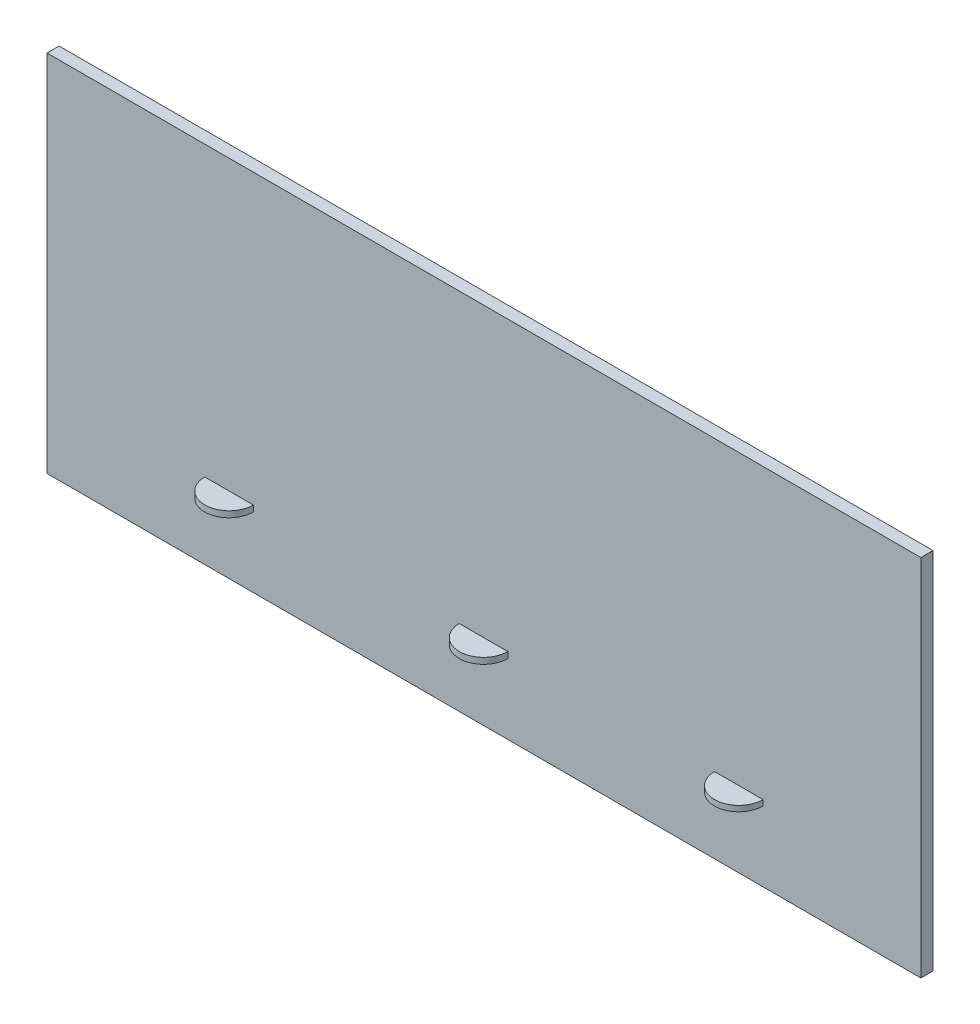
SolidWorks part; units mm, degrees
ref_plane "Front Plane" through (0, 0, 0) normal (0, 0, 1) x (1, 0, 0)
ref_plane "Top Plane" through (0, 0, 0) normal (0, 1, 0) x (1, 0, 0)
ref_plane "Right Plane" through (0, 0, 0) normal (1, 0, 0) x (0, 0, -1)
sketch "Sketch1" plane through (0, 0, 0) normal (0, 0, 1) x (1, 0, 0)
  line L1 (-39.0036, 719.4419) -> (1789.7964, 719.4419)
  line L2 (-39.0036, 719.4419) -> (-39.0036, -42.5581)
  line L3 (-39.0036, -42.5581) -> (1789.7964, -42.5581)
  line L4 (1789.7964, 719.4419) -> (1789.7964, -42.5581)
extrude "Boss-Extrude1" add sketch "Sketch1" along normal blind 25.4
sketch "Sketch4" plane through (0, 0, 25.4) normal (0, 0, 1) x (1, 0, 0)
  line L0 (-39.0036, -42.5581) -> (-39.0036, 109.8419) construction
  line L1 (-39.0036, 719.4419) -> (-39.0036, -42.5581) construction
  line L2 (-39.0036, 109.8419) -> (341.9964, 109.8419) construction
  line L3 (341.9964, 109.8419) -> (392.7964, 109.8419) construction
  line L4 (875.3964, 109.8419) -> (925.4049, 109.8419) construction
  line L5 (341.9964, 109.8419) -> (341.9964, 103.4919) construction
  line L6 (341.9964, 103.4919) -> (341.9964, 116.1919) construction
  line L7 (341.9964, 116.1919) -> (291.1964, 116.1919)
  line L8 (291.1964, 116.1919) -> (291.1964, 103.4919)
  line L9 (291.1964, 103.4919) -> (392.7964, 103.4919)
  line L10 (392.7964, 103.4919) -> (392.7964, 116.1919)
  line L11 (392.7964, 116.1919) -> (341.9964, 116.1919)
  line L22 (874.6049, 116.8638) -> (823.8049, 116.8638)
  line L23 (823.8049, 116.8638) -> (823.8049, 104.1638)
  line L24 (823.8049, 104.1638) -> (925.4049, 104.1638)
  line L25 (925.4049, 104.1638) -> (925.4049, 116.8638)
  line L26 (925.4049, 116.8638) -> (874.6049, 116.8638)
  line L27 (1408.7964, 115.673) -> (1357.9964, 115.673)
  line L28 (1357.9964, 115.673) -> (1357.9964, 104.0108)
  line L29 (1357.9964, 104.0108) -> (1459.5964, 104.0108)
  line L30 (1459.5964, 104.0108) -> (1459.5964, 115.673)
  line L31 (1459.5964, 115.673) -> (1408.7964, 115.673)
  line L32 (823.8049, 109.8419) -> (875.3964, 109.8419) construction
  line L33 (1357.9964, 109.8419) -> (1408.7964, 109.8419) construction
  line L34 (1408.7964, 109.8419) -> (1789.7964, 109.8419) construction
  line L35 (1789.7964, -42.5581) -> (1789.7964, 719.4419) construction
  line L36 (1408.7964, 115.673) -> (1408.7964, 104.0108) construction
  dimension "D1" = 381
  dimension "D2" = 381
  dimension "D3" = 50.8
  dimension "D4" = 152.4
  dimension "D5" = 50.8
  dimension "D6" = 50.8
  dimension "D7" = 101.6
extrude "Boss-Extrude2" add sketch "Sketch4" along normal blind 76.2
sketch "Sketch6" plane through (0, 115.673, 0) normal (0, 1, 0) x (1, 0, 0)
  line L0 (1459.5964, -25.4) -> (1459.5964, -101.6)
  line L1 (1459.5964, -101.6) -> (1357.9964, -101.6)
  line L2 (1357.9964, -101.6) -> (1357.9964, -25.4)
  arc A0 (1459.5964, -25.4) -> (1357.9964, -25.4) centre (1408.7964, -25.4) cw
extrude "Cut-Extrude2" cut sketch "Sketch6" against normal through all
sketch "Sketch7" plane through (0, 116.8638, 0) normal (0, 1, 0) x (1, 0, 0)
  line L0 (925.4049, -25.4) -> (925.4049, -101.6)
  line L1 (925.4049, -101.6) -> (823.8049, -101.6)
  line L2 (823.8049, -101.6) -> (823.8049, -25.4)
  arc A0 (925.4049, -25.4) -> (823.8049, -25.4) centre (874.6049, -25.4) cw
extrude "Cut-Extrude3" cut sketch "Sketch7" against normal blind 116.84
sketch "Sketch8" plane through (0, 116.1919, 0) normal (0, 1, 0) x (1, 0, 0)
  line L0 (392.7964, -25.4) -> (392.7964, -101.6)
  line L1 (392.7964, -101.6) -> (291.1964, -101.6)
  line L2 (291.1964, -101.6) -> (291.1964, -25.4)
  arc A0 (392.7964, -25.4) -> (291.1964, -25.4) centre (341.9964, -25.4) cw
extrude "Cut-Extrude4" cut sketch "Sketch8" against normal blind 116.84
